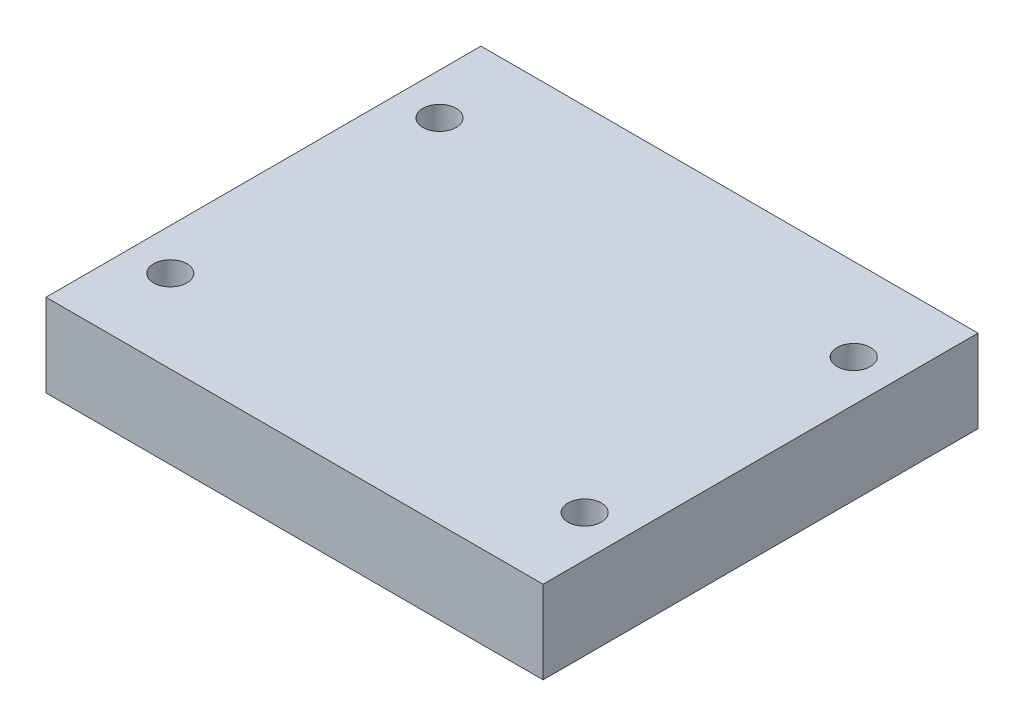
SolidWorks part; units mm, degrees
ref_plane "Front Plane" through (0, 0, 0) normal (0, 0, 1) x (1, 0, 0)
ref_plane "Top Plane" through (0, 0, 0) normal (0, 1, 0) x (1, 0, 0)
ref_plane "Right Plane" through (0, 0, 0) normal (1, 0, 0) x (0, 0, -1)
sketch "Sketch1" plane through (0, 0, 0) normal (0, 1, 0) x (1, 0, 0)
  line L0 (38.1, 33.3375) -> (-38.1, -33.3375) construction
  line L1 (-38.1, -33.3375) -> (38.1, -33.3375)
  line L2 (-38.1, -33.3375) -> (-38.1, 33.3375)
  line L3 (-38.1, 33.3375) -> (38.1, 33.3375)
  line L4 (38.1, -33.3375) -> (38.1, 33.3375)
  dimension "D1" = 76.2
  dimension "D2" = 66.675
extrude "Boss-Extrude1" add sketch "Sketch1" along normal blind 12.7
hole_wizard "#10 Clearance Hole1" positions "Sketch4" profile "Sketch5" hole size "#10" standard "ANSI Inch" end condition through all
sketch "Sketch4" plane through (0, 12.7, 0) normal (0, 1, 0) x (1, 0, 0)
  point P0 (-31.75, 20.6375)
  point P2 (-31.75, -20.6375)
  point P4 (31.75, 20.6375)
  point P6 (31.7748, -20.6375)
sketch "Sketch5" plane through (-31.75, 12.7, -20.6375) normal (1, 0, 0) x (0, 0, 1)
  line L0 (0, 0) -> (0, 12.7)
  line L1 (0, 12.7) -> (2.5527, 12.7)
  line L2 (2.5527, 12.7) -> (2.5527, 0)
  line L5 (2.5527, 0) -> (0, 0)
  line L11 (0, -6.35) -> (0, 107.95) construction
  dimension "Thru Hole Dia." = 5.1054
  dimension "Thru Hole Depth" = 12.7
